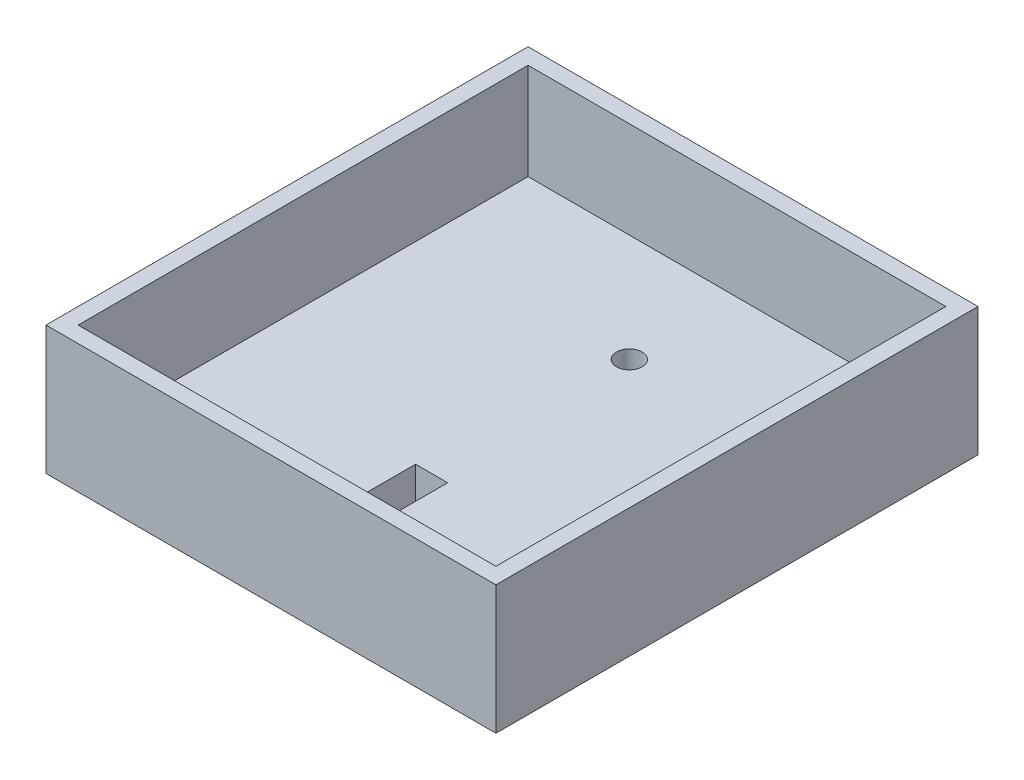
SolidWorks part; units mm, degrees
ref_plane "Front Plane" through (0, 0, 0) normal (0, 0, 1) x (1, 0, 0)
ref_plane "Top Plane" through (0, 0, 0) normal (0, 1, 0) x (1, 0, 0)
ref_plane "Right Plane" through (0, 0, 0) normal (1, 0, 0) x (0, 0, -1)
sketch "Sketch3" plane through (0, 0, 0) normal (0, 1, 0) x (1, 0, 0)
  line L1 (0, 0) -> (140, 0)
  line L2 (0, 0) -> (0, 150)
  line L3 (0, 150) -> (140, 150)
  line L4 (140, 0) -> (140, 150)
  dimension "D1" = 140
  dimension "D2" = 150
extrude "Boss-Extrude1" add sketch "Sketch3" along normal blind 15 contours L3 L4 L1 L2
sketch "Sketch19" plane through (0, 0, 0) normal (0, -1, 0) x (1, 0, 0)
  line L3 (0, 0) -> (0, -150) construction
  line L4 (10, -10) -> (130, -10)
  line L5 (10, -10) -> (10, -140)
  line L6 (10, -140) -> (130, -140)
  line L7 (130, -10) -> (130, -140)
  line L8 (0, -150) -> (140, -150) construction
  line L11 (10, -10) -> (25, -10)
  line L12 (10, -10) -> (10, -25)
  line L13 (10, -25) -> (25, -25)
  line L14 (25, -10) -> (25, -25)
  line L15 (130, -10) -> (115, -10)
  line L16 (130, -10) -> (130, -25)
  line L17 (130, -25) -> (115, -25)
  line L18 (115, -10) -> (115, -25)
  line L19 (130, -140) -> (115, -140)
  line L20 (130, -140) -> (130, -125)
  line L21 (130, -125) -> (115, -125)
  line L22 (115, -140) -> (115, -125)
  line L23 (10, -140) -> (25, -140)
  line L24 (10, -140) -> (10, -125)
  line L25 (10, -125) -> (25, -125)
  line L26 (25, -140) -> (25, -125)
  dimension "D1" = 130
  dimension "D2" = 120
  dimension "D3" = 10
  dimension "D4" = 10
  dimension "D5" = 15
  dimension "D6" = 15
  dimension "D7" = 15
  dimension "D8" = 15
  dimension "D9" = 15
  dimension "D10" = 15
  dimension "D11" = 15
  dimension "D12" = 15
extrude "Cut-Extrude1" cut sketch "Sketch19" against normal blind 5 contours L11 L14 L13 L12
sketch "Sketch20" plane through (0, 0, 0) normal (0, -1, 0) x (1, 0, 0)
  line L0 (140, 0) -> (140, -150) construction
  line L1 (130, -10) -> (115, -10)
  line L2 (130, -10) -> (130, -25)
  line L3 (130, -25) -> (115, -25)
  line L4 (115, -10) -> (115, -25)
  line L5 (0, 0) -> (140, 0) construction
  dimension "D1" = 15
  dimension "D2" = 15
  dimension "D3" = 10
  dimension "D4" = 10
extrude "Cut-Extrude2" cut sketch "Sketch20" against normal blind 5
sketch "Sketch21" plane through (0, 0, 0) normal (0, -1, 0) x (1, 0, 0)
  line L0 (0, 0) -> (0, -150) construction
  line L1 (10, -140) -> (25, -140)
  line L2 (10, -140) -> (10, -125)
  line L3 (10, -125) -> (25, -125)
  line L4 (25, -140) -> (25, -125)
  line L5 (0, -150) -> (140, -150) construction
  dimension "D1" = 15
  dimension "D2" = 15
  dimension "D3" = 10
  dimension "D4" = 10
extrude "Cut-Extrude3" cut sketch "Sketch21" against normal blind 5
sketch "Sketch22" plane through (0, 0, 0) normal (0, -1, 0) x (1, 0, 0)
  line L0 (140, 0) -> (140, -150) construction
  line L1 (130, -125) -> (115, -125)
  line L2 (130, -125) -> (130, -140)
  line L3 (130, -140) -> (115, -140)
  line L4 (115, -125) -> (115, -140)
  line L5 (0, -150) -> (140, -150) construction
  dimension "D1" = 15
  dimension "D2" = 15
  dimension "D3" = 10
  dimension "D4" = 10
extrude "Cut-Extrude4" cut sketch "Sketch22" against normal blind 5
sketch "Sketch24" plane through (0, 0, 0) normal (0, -1, 0) x (1, 0, 0)
  line L0 (140, 0) -> (140, -150) construction
  line L1 (60, -65) -> (80, -65)
  line L2 (60, -65) -> (60, -85)
  line L3 (60, -85) -> (80, -85)
  line L4 (80, -65) -> (80, -85)
  line L5 (0, 0) -> (140, 0) construction
  dimension "D1" = 20
  dimension "D2" = 20
  dimension "D3" = 60
  dimension "D4" = 65
extrude "Cut-Extrude6" cut sketch "Sketch24" against normal blind 5 contours L1 L4 L3 L2
sketch "Sketch25" plane through (0, 0, 0) normal (0, -1, 0) x (-1, 0, 0)
  line L0 (0, 150) -> (-140, 150) construction
  line L1 (-60, 65) -> (-80, 65) construction
  line L2 (-75, 50) -> (-65, 50)
  line L3 (-75, 50) -> (-75, 30)
  line L4 (-75, 30) -> (-65, 30)
  line L5 (-65, 50) -> (-65, 30)
  line L6 (0, 0) -> (-140, 0) construction
  circle A0 centre (-70, 111.5) radius 4
  point P4 (-70, 150)
  point P13 (-70, 0)
  point P14 (-70, 30)
  dimension "D1" = 8
  dimension "D2" = 38.5
  dimension "D3" = 20
  dimension "D4" = 10
  dimension "D5" = 15
extrude "Cut-Extrude7" cut sketch "Sketch25" against normal through all contours A0
sketch "Sketch26" plane through (0, 0, 0) normal (0, -1, 0) x (1, 0, 0)
  line L0 (60, -65) -> (80, -65) construction
  line L1 (65, -50) -> (75, -50)
  line L2 (65, -50) -> (65, -30)
  line L3 (65, -30) -> (75, -30)
  line L4 (75, -50) -> (75, -30)
  line L5 (0, 0) -> (140, 0) construction
  point P8 (70, 0)
  point P9 (70, -30)
  dimension "D1" = 20
  dimension "D2" = 10
  dimension "D3" = 15
extrude "Cut-Extrude8" cut sketch "Sketch26" against normal through all
sketch "Sketch27" plane through (0, 15, 0) normal (0, 1, 0) x (1, 0, 0)
  line L0 (0, 0) -> (140, 0) construction
  line L1 (0, 150) -> (5, 150)
  line L2 (0, 150) -> (0, 0)
  line L3 (0, 0) -> (5, 0)
  line L4 (5, 150) -> (5, 0)
  dimension "D1" = 5
extrude "Boss-Extrude2" add sketch "Sketch27" along normal blind 30
sketch "Sketch28" plane through (0, 15, 0) normal (0, 1, 0) x (1, 0, 0)
  line L0 (5, 0) -> (5, 150) construction
  line L1 (140, 150) -> (5, 150)
  line L2 (140, 150) -> (140, 145)
  line L3 (140, 145) -> (5, 145)
  line L4 (5, 150) -> (5, 145)
  dimension "D1" = 5
extrude "Boss-Extrude3" add sketch "Sketch28" along normal blind 30
sketch "Sketch29" plane through (0, 15, 0) normal (0, 1, 0) x (1, 0, 0)
  line L0 (5, 145) -> (140, 145) construction
  line L1 (140, 0) -> (135, 0)
  line L2 (140, 0) -> (140, 145)
  line L3 (140, 145) -> (135, 145)
  line L4 (135, 0) -> (135, 145)
  dimension "D1" = 5
extrude "Boss-Extrude4" add sketch "Sketch29" along normal blind 30
sketch "Sketch30" plane through (0, 15, 0) normal (0, 1, 0) x (1, 0, 0)
  line L0 (135, 145) -> (135, 0) construction
  line L1 (5, 0) -> (135, 0)
  line L2 (5, 0) -> (5, 5)
  line L3 (5, 5) -> (135, 5)
  line L4 (135, 0) -> (135, 5)
  dimension "D1" = 5
extrude "Boss-Extrude5" add sketch "Sketch30" along normal blind 30
chamfer "Chamfer2" distance 5 angle 45 4 edges at (140, 0, -75) (70, 0, -150) (0, 0, -75) (70, 0, 0)
